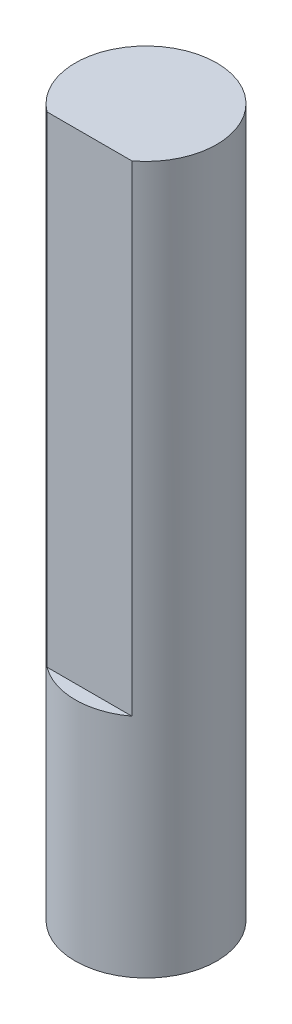
SolidWorks part; units mm, degrees
ref_plane "Спереди" through (0, 0, 0) normal (0, 0, 1) x (1, 0, 0)
ref_plane "Сверху" through (0, 0, 0) normal (0, 1, 0) x (1, 0, 0)
ref_plane "Справа" through (0, 0, 0) normal (1, 0, 0) x (0, 0, -1)
sketch "Эскиз1" plane through (0, 0, 0) normal (0, 1, 0) x (1, 0, 0)
  circle A0 centre (0, 0) radius 2.5
  dimension "D1" = 5
extrude "Бобышка-Вытянуть1" add sketch "Эскиз1" along normal blind 25
sketch "Эскиз2" plane through (0, 25, 0) normal (0, 1, 0) x (1, 0, 0)
  line L0 (0, 2.5) -> (0, -2) construction
  line L1 (-1.5, -2) -> (1.5, -2)
  circle A0 centre (0, 0) radius 2.5
  circle M2 centre (0, 0) radius 2.5
  dimension "D2" = 5
  dimension "D1" = 4.5
extrude "Вырез-Вытянуть1" cut sketch "Эскиз2" against normal blind 17 contours L1 M2
